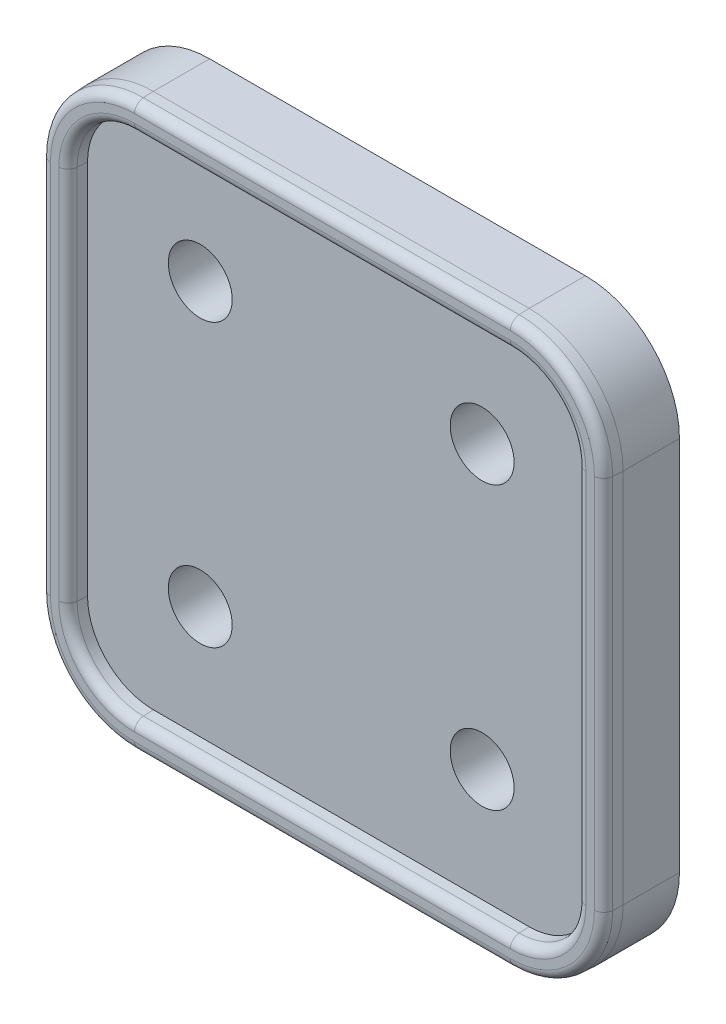
SolidWorks part; units mm, degrees
material "ABS"
ref_plane "Front Plane" through (0, 0, 0) normal (0, 0, 1) x (1, 0, 0)
ref_plane "Top Plane" through (0, 0, 0) normal (0, 1, 0) x (1, 0, 0)
ref_plane "Right Plane" through (0, 0, 0) normal (1, 0, 0) x (0, 0, -1)
sketch "Sketch1" plane through (0, 0, 0) normal (0, 0, 1) x (1, 0, 0)
  line L0 (5, 30) -> (25, 30)
  line L1 (5, 0) -> (25, 0)
  line L2 (0, 5) -> (0, 25)
  line L3 (30, 5) -> (30, 25)
  arc A0 (0, 5) -> (5, 0) centre (5, 5) ccw
  arc A1 (30, 5) -> (25, 0) centre (25, 5) cw
  arc A2 (30, 25) -> (25, 30) centre (25, 25) ccw
  arc A4 (5, 30) -> (0, 25) centre (5, 25) ccw
  point P8 (0, 0)
  point P11 (30, 0)
  point P19 (0, 30)
  dimension "D4" = 5
  dimension "D1" = 30
  dimension "D2" = 30
extrude "Boss-Extrude1" add sketch "Sketch1" along normal blind 3
sketch "Sketch2" plane through (0, 0, 3) normal (0, 0, 1) x (1, 0, 0)
  line L0 (22.5, 7.5) -> (7.5, 7.5) construction
  line L1 (22.5, 7.5) -> (22.5, 22.5) construction
  line L3 (22.5, 22.5) -> (7.5, 22.5) construction
  line L4 (7.5, 7.5) -> (7.5, 22.5) construction
  circle A0 centre (22.5, 22.5) radius 1.7
  circle A1 centre (7.5, 7.5) radius 1.7
  circle A2 centre (7.5, 22.5) radius 1.7
  circle A3 centre (22.5, 7.5) radius 1.7
  dimension "D3" = 15
  dimension "D5" = 15
extrude "Cut-Extrude1" cut sketch "Sketch2" against normal through all
sketch "Sketch3" plane through (0, 0, 3) normal (0, 0, 1) x (1, 0, 0)
  line L0 (28.5, 25) -> (28.5, 5)
  line L1 (5, 28.5) -> (25, 28.5)
  line L2 (5, 1.5) -> (25, 1.5)
  line L3 (1.5, 5) -> (1.5, 25)
  line L4 (30, 5) -> (30, 25)
  line L10 (5, 0) -> (25, 0)
  line L11 (30, 5) -> (30, 25)
  line L12 (25, 30) -> (5, 30)
  line L13 (25, 30) -> (5, 30)
  line L14 (0, 25) -> (0, 5)
  line L15 (5, 0) -> (25, 0)
  line L19 (0, 25) -> (0, 5)
  arc A0 (25, 28.5) -> (28.5, 25) centre (25, 25) cw
  arc A1 (28.5, 5) -> (25, 1.5) centre (25, 5) cw
  arc A2 (5, 1.5) -> (1.5, 5) centre (5, 5) cw
  arc A3 (1.5, 25) -> (5, 28.5) centre (5, 25) cw
  arc A4 (30, 25) -> (25, 30) centre (25, 25) ccw
  arc A10 (0, 5) -> (5, 0) centre (5, 5) ccw
  arc A11 (25, 0) -> (30, 5) centre (25, 5) ccw
  arc A12 (30, 25) -> (25, 30) centre (25, 25) ccw
  arc A14 (5, 30) -> (0, 25) centre (5, 25) ccw
  arc A15 (0, 5) -> (5, 0) centre (5, 5) ccw
  arc A16 (25, 0) -> (30, 5) centre (25, 5) ccw
  arc A19 (5, 30) -> (0, 25) centre (5, 25) ccw
  dimension "D4" = 1.5
  dimension "D2" = 1.5
  dimension "D3" = 1.5
  dimension "D5" = 1.5
  dimension "D1" = 0
extrude "Boss-Extrude2" add sketch "Sketch3" along normal blind 1 draft 3
fillet "Fillet1" radius 0.5 16 edges at (0.0524, 15, 4) (1.5015, 28.4985, 4) (28.4985, 1.5015, 4) (15, 0.0524, 4) (1.5015, 1.5015, 4) (27.5119, 2.4881, 4) (28.5524, 15, 4) (27.5119, 27.5119, 4) (15, 28.5524, 4) (15, 29.9476, 4) (28.4985, 28.4985, 4) (29.9476, 15, 4) (2.4881, 27.5119, 4) (1.4476, 15, 4) (2.4881, 2.4881, 4) (15, 1.4476, 4)
